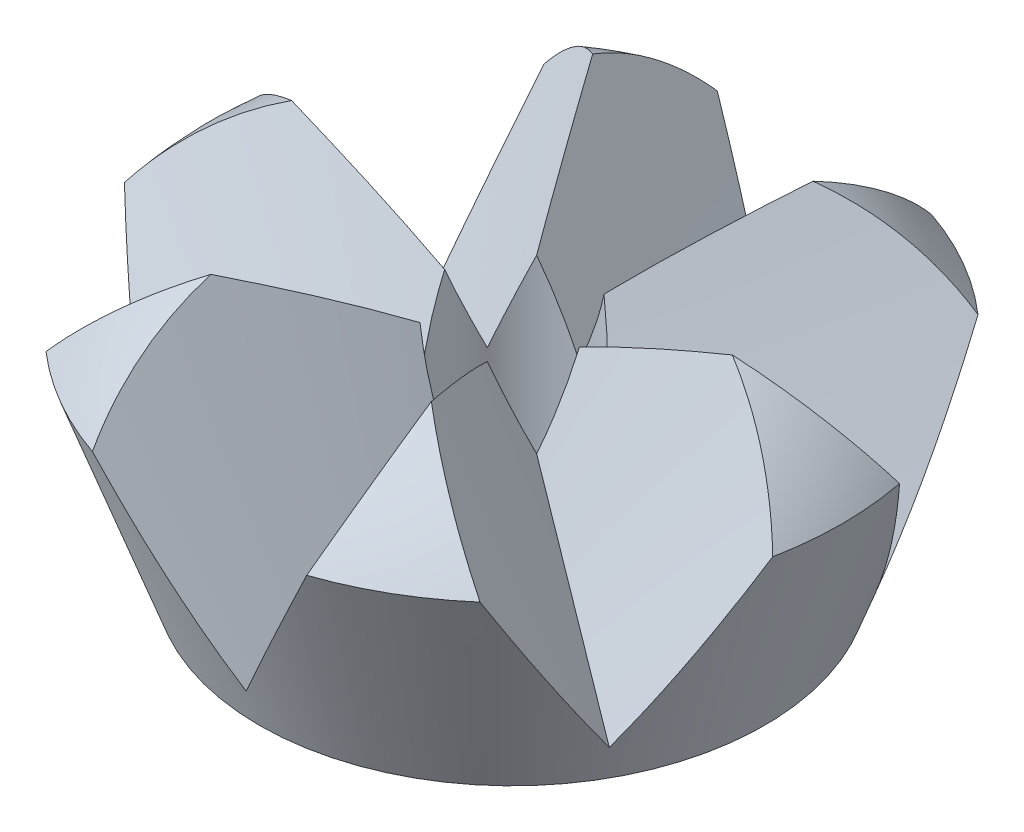
SolidWorks part; units mm, degrees
ref_plane "Front Plane" through (0, 0, 0) normal (0, 0, 1) x (1, 0, 0)
ref_plane "Top Plane" through (0, 0, 0) normal (0, 1, 0) x (1, 0, 0)
ref_plane "Right Plane" through (0, 0, 0) normal (1, 0, 0) x (0, 0, -1)
sketch "Sketch1" plane through (0, 0, 0) normal (0, 0, 1) x (1, 0, 0)
  line L1 (15, 0) -> (19.6173, 12.6859)
  line L6 (0, 0) -> (0, 21.954) construction
  line L7 (4, 0) -> (15, 0)
  line L8 (4, 0) -> (4, 20.0126)
  arc A1 (19.6173, 12.6859) -> (4, 20.0126) centre (4.8638, 1.5459) ccw
  dimension "D1" = 15
  dimension "D2" = 13.5
  dimension "D3" = 4
revolve "Revolve1" add sketch "Sketch1" angle 360 about L6
sketch "Sketch2" plane through (0, 0, 0) normal (0, 0, 1) x (1, 0, 0)
  line L0 (0, 0) -> (0, 25.5731) construction
  line L2 (0, 11.5993) -> (-4.0489, 21.3182)
  line L3 (-4.0489, 21.3182) -> (0, 25.5731)
  line L4 (4.0489, 21.3182) -> (0, 25.5731)
  line L5 (0, 11.5993) -> (4.0489, 21.3182)
  point P5 (0, 0)
  point P6 (0, 0)
  point P7 (0, 0)
  point P8 (-4.0489, 21.3182)
ref_plane "Plane1" through (0, -4.8209, 13.2453) normal (0, -0.342, 0.9397) x (1, 0, 0)
sketch "Sketch3" plane through (0, -4.8209, 13.2453) normal (0, -0.342, 0.9397) x (1, 0, 0)
  line L1 (0, 0) -> (0, 28.4708) construction
  line L2 (0, 7.4248) -> (-10.2025, 24.4112)
  line L3 (-10.2025, 24.4112) -> (0, 28.4708)
  line L4 (10.2025, 24.4112) -> (0, 28.4708)
  line L5 (0, 7.4248) -> (10.2025, 24.4112)
sketch3d "3DSketch4"
  point P0 (0, 25.5731, 0)
  point P3 (0, 0, 0)
loft "Cut-Loft6" cut profiles "Sketch2", "Sketch3"
pattern_circular "CirPattern2" count 6 over 360 about axis through (0, 0, 0) along (0, 1, 0) of "Cut-Loft6"
